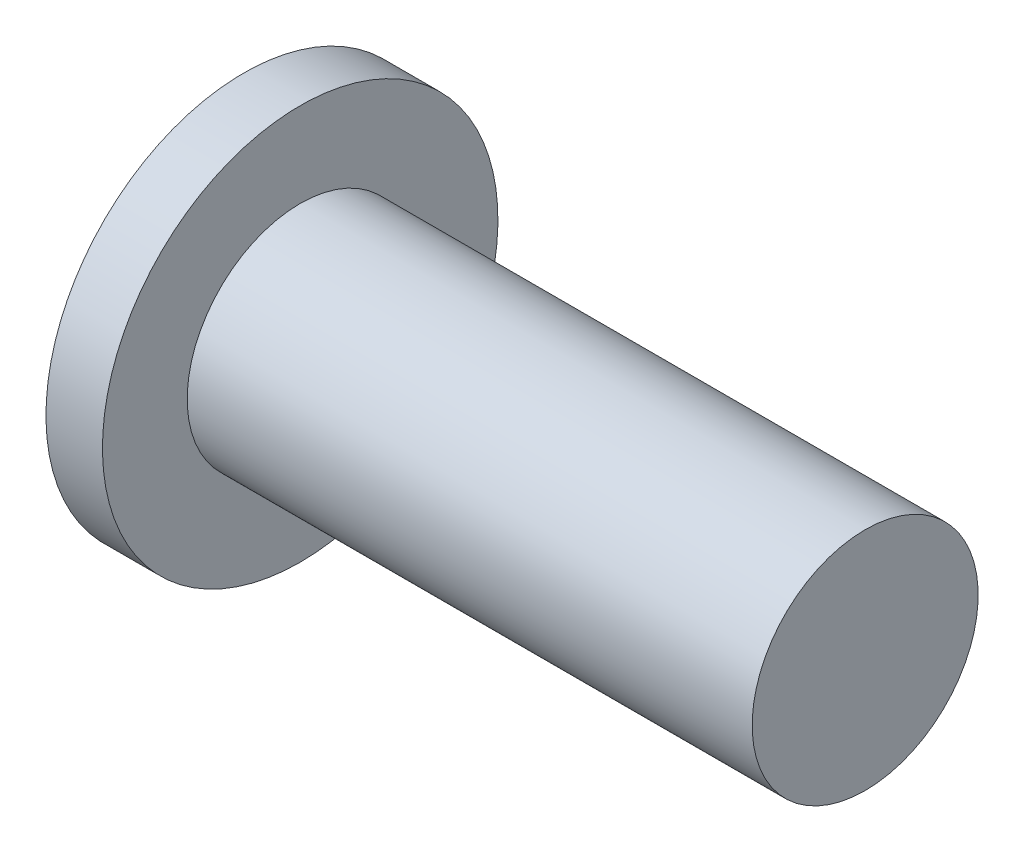
SolidWorks part; units mm, degrees
ref_plane "前视基准面" through (0, 0, 0) normal (0, 0, 1) x (1, 0, 0)
ref_plane "上视基准面" through (0, 0, 0) normal (0, 1, 0) x (1, 0, 0)
ref_plane "右视基准面" through (0, 0, 0) normal (1, 0, 0) x (0, 0, -1)
other "Configuration Table"
sketch "草图1" plane through (0, 0, 0) normal (0, 0, 1) x (1, 0, 0)
  line L0 (0, 0) -> (10, 0)
  line L1 (0, 0) -> (0, 1.5)
  line L2 (0, 1.5) -> (-1, 1.5)
  line L3 (10, 0) -> (10, -2)
  line L4 (10, -2) -> (8.7823, -2) construction
  line L5 (-1, 1.5) -> (-1, -2)
  line L6 (-1, -2) -> (10, -2)
  dimension "D1" = 10
  dimension "D2" = 1.5
  dimension "D3" = 1
  dimension "D4" = 2
revolve "旋转1" add sketch "草图1" angle 360 about L6
